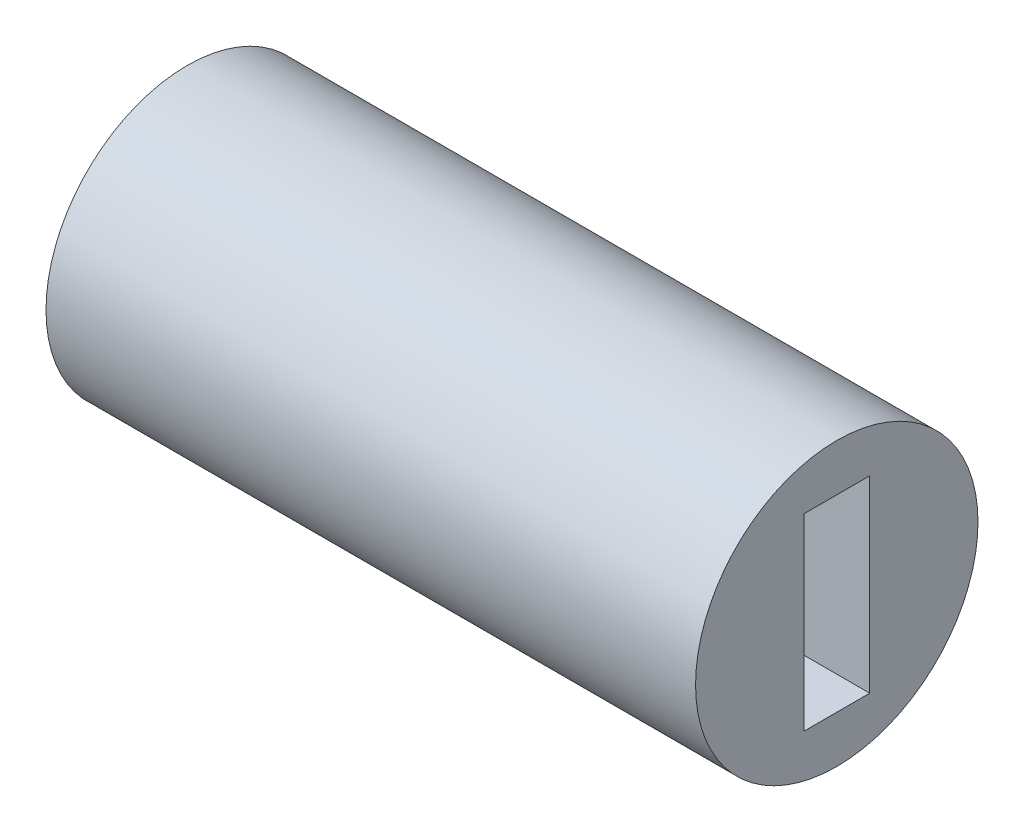
SolidWorks part; units mm, degrees
ref_plane "Front Plane" through (0, 0, 0) normal (0, 0, 1) x (1, 0, 0)
ref_plane "Top Plane" through (0, 0, 0) normal (0, 1, 0) x (1, 0, 0)
ref_plane "Right Plane" through (0, 0, 0) normal (1, 0, 0) x (0, 0, -1)
sketch "Sketch1" plane through (0, 0, 0) normal (1, 0, 0) x (0, 0, -1)
  line L0 (-0.7, 0) -> (0.7, 0) construction
  line L1 (-0.7, 2) -> (0.7, 2)
  line L2 (-0.7, 2) -> (-0.7, -2)
  line L3 (-0.7, -2) -> (0.7, -2)
  line L4 (0.7, 2) -> (0.7, -2)
  circle A0 centre (0, 0) radius 3
  point P9 (0, 0)
  dimension "D3" = 6
  dimension "D1" = 1.4
  dimension "D2" = 4
extrude "Boss-Extrude1" add sketch "Sketch1" along normal blind 10
sketch "Sketch2" plane through (0, 0, 0) normal (-1, 0, 0) x (0, 0, 1)
  line L0 (-0.7, 0) -> (0.7, 0) construction
  line L1 (-0.7, 2.5) -> (0.7, 2.5)
  line L2 (-0.7, 2.5) -> (-0.7, -2.5)
  line L3 (-0.7, -2.5) -> (0.7, -2.5)
  line L4 (0.7, 2.5) -> (0.7, -2.5)
  line L5 (-0.7, -2) -> (-0.7, 2) construction
  circle A0 centre (0, 0) radius 3 construction
  circle A1 centre (0, 0) radius 3
  point P9 (0, 0)
  dimension "D1" = 5
extrude "Boss-Extrude2" add sketch "Sketch2" along normal blind 3.8
